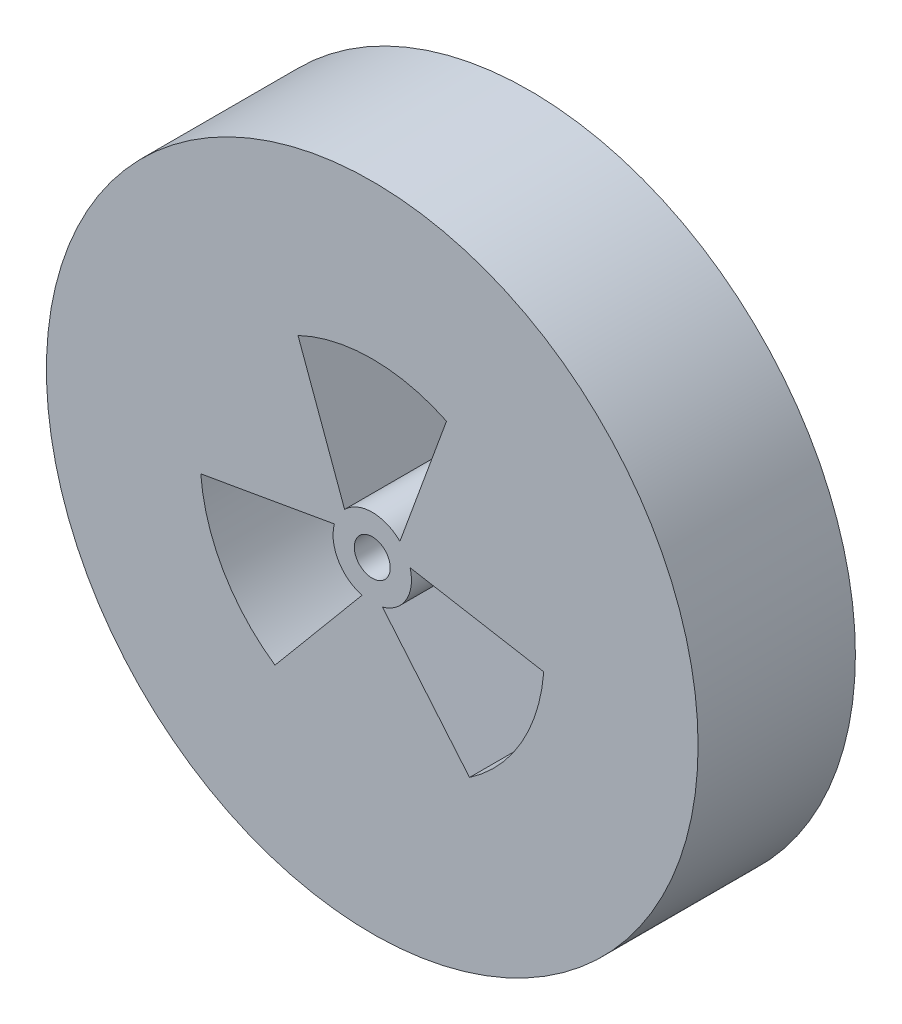
SolidWorks part; units mm, degrees
ref_plane "Front Plane" through (0, 0, 0) normal (0, 0, 1) x (1, 0, 0)
ref_plane "Top Plane" through (0, 0, 0) normal (0, 1, 0) x (1, 0, 0)
ref_plane "Right Plane" through (0, 0, 0) normal (1, 0, 0) x (0, 0, -1)
sketch "Sketch1" plane through (0, 0, 0) normal (0, 0, 1) x (1, 0, 0)
  circle A0 centre (0, 0) radius 72.5
  circle A1 centre (0, 0) radius 4
  dimension "D1" = 145
extrude "Boss-Extrude1" add sketch "Sketch1" along normal blind 35
sketch "Sketch3" plane through (0, 0, 35) normal (0, 0, 1) x (1, 0, 0)
  line L0 (0, 38.2722) -> (0, 8.7229)
  line L1 (-6.1553, 6.1807) -> (-16.519, 34.5237)
  arc A0 (-6.1553, 6.1807) -> (0, 8.7229) centre (0, 0) cw
  arc A2 (-16.519, 34.5237) -> (0, 38.2722) centre (0, 0) cw
  point P4 (-16.519, 34.5237)
  dimension "D1" = 0
extrude "Cut-Extrude1" cut sketch "Sketch3" against normal blind 35
mirror "Mirror1" about plane through (0, 38.2722, 0) normal (1, 0, 0) of "Cut-Extrude1"
pattern_circular "CirPattern6" count 3 over 360 about axis through (0, 0, 0) along (0, 0, 1) of "Cut-Extrude1"
mirror "Mirror2" about plane through (33.1447, -19.1361, 0) normal (-0.5, -0.866, 0) of "CirPattern6", "Cut-Extrude1"
